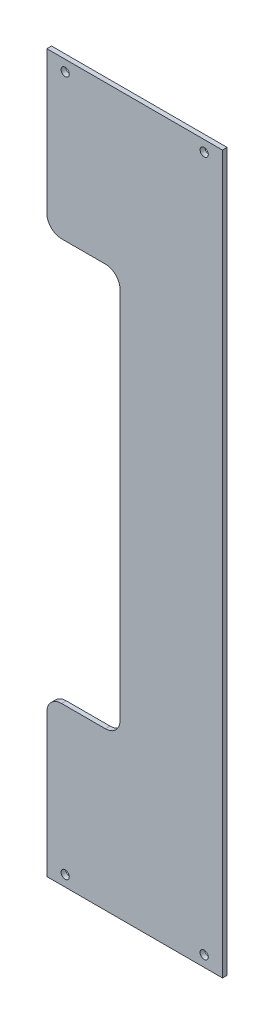
SolidWorks part; units mm, degrees
ref_plane "Front Plane" through (0, 0, 0) normal (1, 0, 0) x (0, 1, 0)
ref_plane "Top Plane" through (0, 0, 0) normal (0, 0, 1) x (0, 1, 0)
ref_plane "Right Plane" through (0, 0, 0) normal (0, 1, 0) x (-1, 0, 0)
sketch "Sketch1" plane through (0, 0, 0) normal (0, 0, 1) x (0, 1, 0)
  line L1 (-250, -60) -> (250, -60)
  line L2 (-250, -60) -> (-250, 60)
  line L3 (-250, 60) -> (250, 60)
  line L4 (250, -60) -> (250, 60)
  line L5 (-250, -60) -> (250, 60) construction
  line L6 (-250, 60) -> (250, -60) construction
  line L7 (237.5, -47.5) -> (-237.5, -47.5) construction
  line L8 (237.5, -47.5) -> (237.5, 47.5) construction
  line L9 (237.5, 47.5) -> (-237.5, 47.5) construction
  line L10 (-237.5, -47.5) -> (-237.5, 47.5) construction
  line L11 (237.5, -47.5) -> (-237.5, 47.5) construction
  line L12 (237.5, 47.5) -> (-237.5, -47.5) construction
  circle A0 centre (-237.5, 47.5) radius 2.8
  circle A1 centre (-237.5, -47.5) radius 2.8
  circle A2 centre (237.5, 47.5) radius 2.8
  circle A3 centre (237.5, -47.5) radius 2.8
  point P0 (0, 0)
  point P6 (0, 0)
  dimension "D3" = 5.6
  dimension "D1" = 120
  dimension "D2" = 500
  dimension "D4" = 12.5
  dimension "D5" = 12.5
extrude "Boss-Extrude1" add sketch "Sketch1" along normal blind 3.175
sketch "Sketch2" plane through (0, 0, 3.175) normal (0, 0, 1) x (1, 0, 0)
  line L0 (-60, 250) -> (-60, -250) construction
  line L1 (-60, 137.5) -> (-10, 137.5)
  line L2 (-60, 137.5) -> (-60, -137.5)
  line L3 (-60, -137.5) -> (-10, -137.5)
  line L4 (-10, 137.5) -> (-10, -137.5)
  line L5 (-60, 137.5) -> (-10, -137.5) construction
  line L6 (-60, -137.5) -> (-10, 137.5) construction
  line L7 (-35, 0) -> (0, 0) construction
  point P4 (-35, 0)
  dimension "D1" = 275
  dimension "D2" = 50
extrude "Cut-Extrude1" cut sketch "Sketch2" against normal through all
fillet "Fillet1" radius 10 4 edges at (-10, 137.5, 1.5875) (-60, 137.5, 1.5875) (-10, -137.5, 1.5875) (-60, -137.5, 1.5875)
sketch "Sketch3" plane through (0, 0, 3.175) normal (0, 0, 1) x (1, 0, 0)
  line L0 (-60, 250) -> (-60, 147.5) construction
  line L1 (-60, 245) -> (60, 245)
  line L2 (-60, 245) -> (-60, 250)
  line L3 (-60, 250) -> (60, 250)
  line L4 (60, 245) -> (60, 250)
  line L5 (-60, 245) -> (60, 250) construction
  line L6 (-60, 250) -> (60, 245) construction
  line L7 (60, -250) -> (60, 250) construction
  line L8 (-60, -250) -> (60, -250)
  line L9 (-60, -250) -> (-60, -245)
  line L10 (-60, -245) -> (60, -245)
  line L11 (60, -250) -> (60, -245)
  line L12 (-60, -250) -> (60, -245) construction
  line L13 (-60, -245) -> (60, -250) construction
  point P4 (0, 247.5)
  point P12 (0, -247.5)
  dimension "D1" = 5
  dimension "D2" = 5
extrude "Cut-Extrude2" cut sketch "Sketch3" against normal through all
